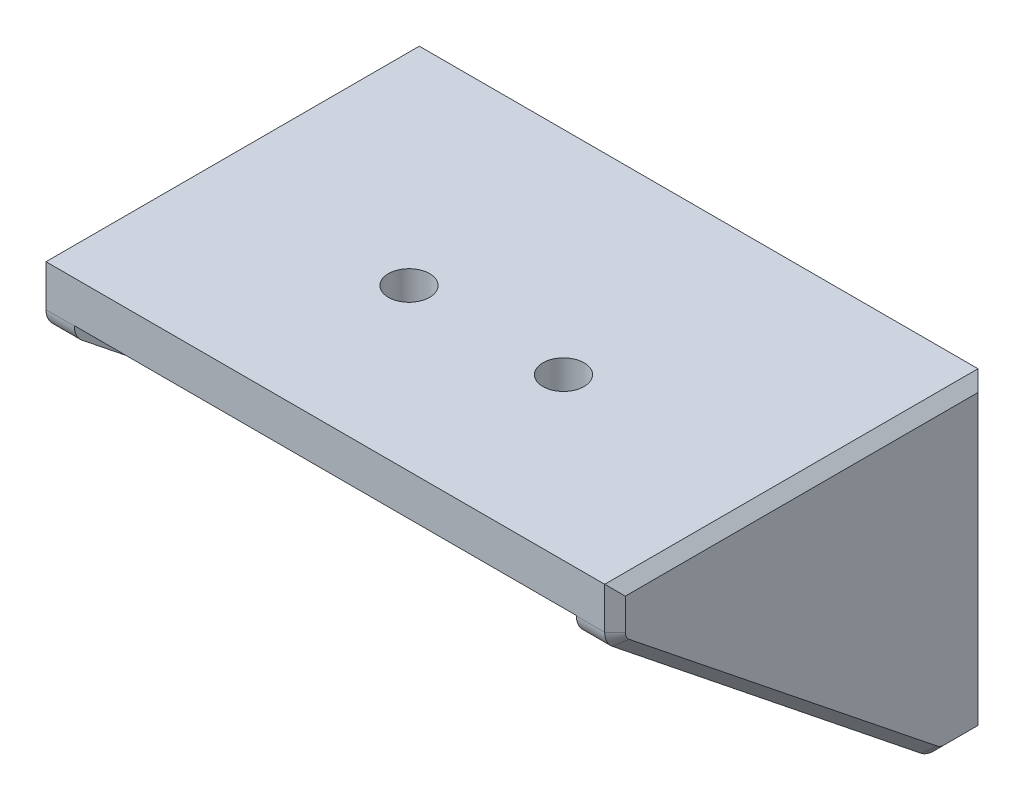
SolidWorks part; units mm, degrees
ref_plane "前视基准面" through (0, 0, 0) normal (0, 0, 1) x (1, 0, 0)
ref_plane "上视基准面" through (0, 0, 0) normal (0, 1, 0) x (1, 0, 0)
ref_plane "右视基准面" through (0, 0, 0) normal (1, 0, 0) x (0, 0, -1)
other "Configuration Table"
sketch "草图1" plane through (0, 0, 0) normal (0, 1, 0) x (1, 0, 0)
  line L0 (-7.6, -2) -> (7.6, -2) construction
  line L1 (0, 19.3574) -> (0, -19.3574) construction
  line L3 (-19.5, -14.5) -> (19.5, -14.5)
  line L4 (-19.5, -14.5) -> (-19.5, 14.5)
  line L5 (-19.5, 14.5) -> (19.5, 14.5)
  line L6 (19.5, -14.5) -> (19.5, 14.5)
  line L7 (-19.5, -14.5) -> (19.5, 14.5) construction
  line L8 (-19.5, 14.5) -> (19.5, -14.5) construction
  circle A0 centre (-6, -2) radius 1.6
  circle A1 centre (6, -2) radius 1.6
  point P1 (0, 0)
  dimension "D2" = 3.2
  dimension "D1" = 12
  dimension "D3" = 29
  dimension "D4" = 39
  dimension "D5" = 2
extrude "凸台-拉伸1" add sketch "草图1" along normal blind 4
sketch "草图2" plane through (0, 0, 0) normal (0, -1, 0) x (-1, 0, 0)
  line L0 (-19.5, 14.5) -> (19.5, 14.5) construction
  line L1 (-19.5, 14.5) -> (19.5, 14.5)
  line L2 (-19.5, 10.5) -> (19.5, 10.5)
  line L3 (-19.5, 10.5) -> (-19.5, 14.5)
  line L5 (19.5, 10.5) -> (19.5, 14.5)
  dimension "D1" = 4
extrude "凸台-拉伸2" add sketch "草图2" along normal blind 20
sketch "草图3" plane through (0, 0, -10.5) normal (0, 0, 1) x (1, 0, 0)
  line L0 (0, 14.0724) -> (0, -28.9912) construction
  line L1 (-20.4001, -10) -> (23.554, -10) construction
  line L2 (-19.5, 0) -> (19.5, 0) construction
  line L3 (19.5, -20) -> (-19.5, -20) construction
  circle A0 centre (16, -4) radius 1.35
  circle A1 centre (16, -16) radius 1.35
  circle A2 centre (-16, -16) radius 1.35
  circle A3 centre (-16, -4) radius 1.35
  dimension "D1" = 12
  dimension "D2" = 32
  dimension "D3" = 2.7
extrude "切除-拉伸1" cut sketch "草图3" against normal blind 4
ref_plane "基准面1" through (0, 0, 0) normal (1, 0, 0) x (0, 0, -1)
sketch "草图4" plane through (19.5, 0, 0) normal (1, 0, 0) x (0, 0, -1)
  line L0 (-14.5, 0) -> (10.5, -20)
  line L6 (-14.5, 0) -> (10.5, 0)
  line L7 (10.5, 0) -> (10.5, -20)
  line L8 (10.5, -20) -> (14.5, -20)
  line L9 (14.5, -20) -> (14.5, 4)
  line L10 (14.5, 4) -> (-14.5, 4)
  line L11 (-14.5, 4) -> (-14.5, 0)
  line L14 (10.5, -20) -> (14.5, -20)
  line L15 (14.5, -20) -> (14.5, 4)
  line L16 (14.5, 4) -> (-14.5, 4)
  line L17 (-14.5, 4) -> (-14.5, 0)
  dimension "D1" = 0
extrude "凸台-拉伸3" add sketch "草图4" along normal blind 3
mirror "镜向1" about plane through (0, 0, 0) normal (1, 0, 0) of "凸台-拉伸3"
chamfer "倒角1" distance 0.8 angle 45 7 edges at (-22.5, 4, 0) (-22.5, -8, -14.5) (0, -20, -14.5) (22.5, 4, 0) (22.5, -8, -14.5) (0, 0, 14.5) (0, -20, -10.5)
fillet "圆角1" radius 1.6 4 edges at (21, 0, 14.5) (21, -20, -10.5) (-21, 0, 14.5) (-21, -20, -10.5)
chamfer "倒角3" distance 0.8 angle 45 10 edges at (22.5, 1.9845, 14.5) (22.5, -20, -12.3806) (22.5, 0.0759, 14.3421) (22.5, -19.9098, -10.5316) (22.5, -10.0649, 1.9189) (-22.5, -20, -12.3806) (-22.5, -19.9098, -10.5316) (-22.5, -10.0649, 1.9189) (-22.5, 0.0759, 14.3421) (-22.5, 1.9845, 14.5)
